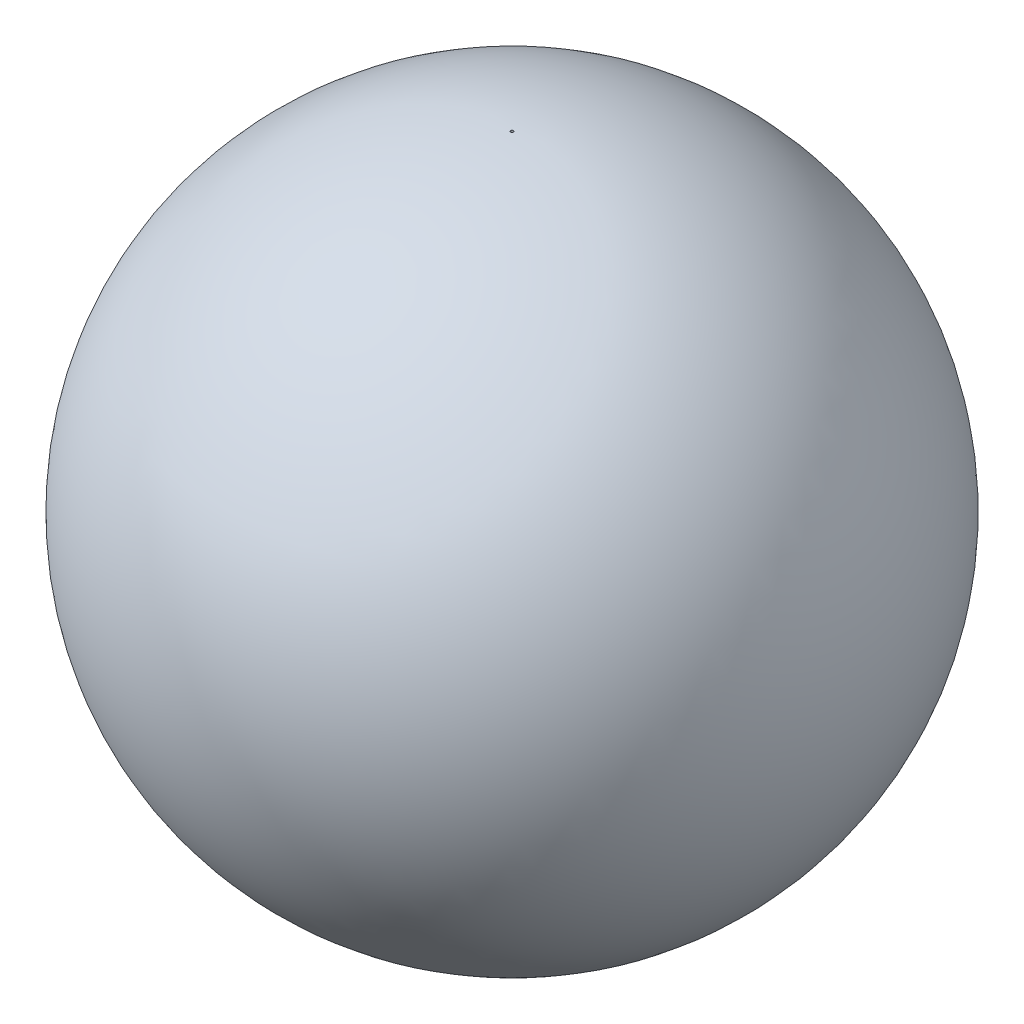
SolidWorks part; units mm, degrees
ref_plane "Front Plane" through (0, 0, 0) normal (0, 0, 1) x (1, 0, 0)
ref_plane "Top Plane" through (0, 0, 0) normal (0, 1, 0) x (1, 0, 0)
ref_plane "Right Plane" through (0, 0, 0) normal (1, 0, 0) x (0, 0, -1)
sketch "Sketch1" plane through (0, 0, 0) normal (0, 1, 0) x (1, 0, 0)
  line L0 (0, -298.45) -> (0, 298.45)
  circle A0 centre (0, 0) radius 298.45
  circle A1 centre (0, 0) radius 292.1
  dimension "D1" = 596.9
  dimension "D2" = 6.35
ref_plane "Plane2" through (0, 0, 25.4) normal (0, 0, 1) x (1, 0, 0)
ref_axis "Axis2" through (0, 0, 0) along (0, 0, 1)
revolve "Revolve3" add sketch "Sketch1" angle 360 about axis through (0, 0, 0) along (0, 0, 1)
sketch "Sketch2" plane through (0, 0, 0) normal (0, 1, 0) x (1, 0, 0)
  circle A0 centre (0, 0) radius 1.27
  dimension "D1" = 2.54
extrude "Cut-Extrude1" cut sketch "Sketch2" against normal blind 401.828 and the other way blind 381.508
